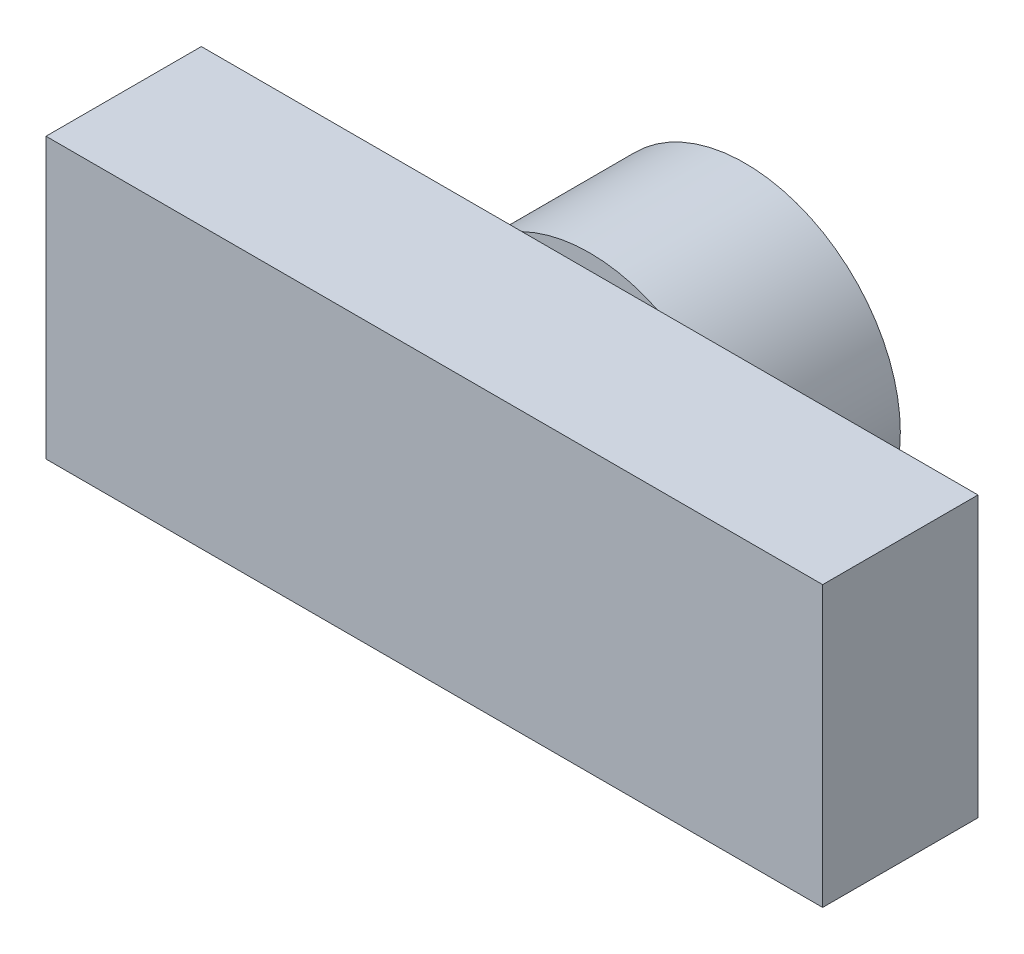
SolidWorks part; units mm, degrees
ref_plane "Front Plane" through (0, 0, 0) normal (0, 0, 1) x (1, 0, 0)
ref_plane "Top Plane" through (0, 0, 0) normal (0, 1, 0) x (1, 0, 0)
ref_plane "Right Plane" through (0, 0, 0) normal (1, 0, 0) x (0, 0, -1)
sketch "Sketch1" plane through (0, 0, 0) normal (0, 0, 1) x (1, 0, 0)
  circle A0 centre (0, 0) radius 5
  dimension "D1" = 10
extrude "Boss-Extrude1" add sketch "Sketch1" along normal blind 5
sketch "Sketch2" plane through (0, 0, 5) normal (0, 0, 1) x (1, 0, 0)
  line L1 (-12.5, -4.5) -> (12.5, -4.5)
  line L2 (-12.5, -4.5) -> (-12.5, 4.5)
  line L3 (-12.5, 4.5) -> (12.5, 4.5)
  line L4 (12.5, -4.5) -> (12.5, 4.5)
  line L5 (-12.5, -4.5) -> (12.5, 4.5) construction
  line L6 (-12.5, 4.5) -> (12.5, -4.5) construction
  point P0 (0, 0)
  dimension "D1" = 25
  dimension "D2" = 9
extrude "Boss-Extrude2" add sketch "Sketch2" along normal blind 5
